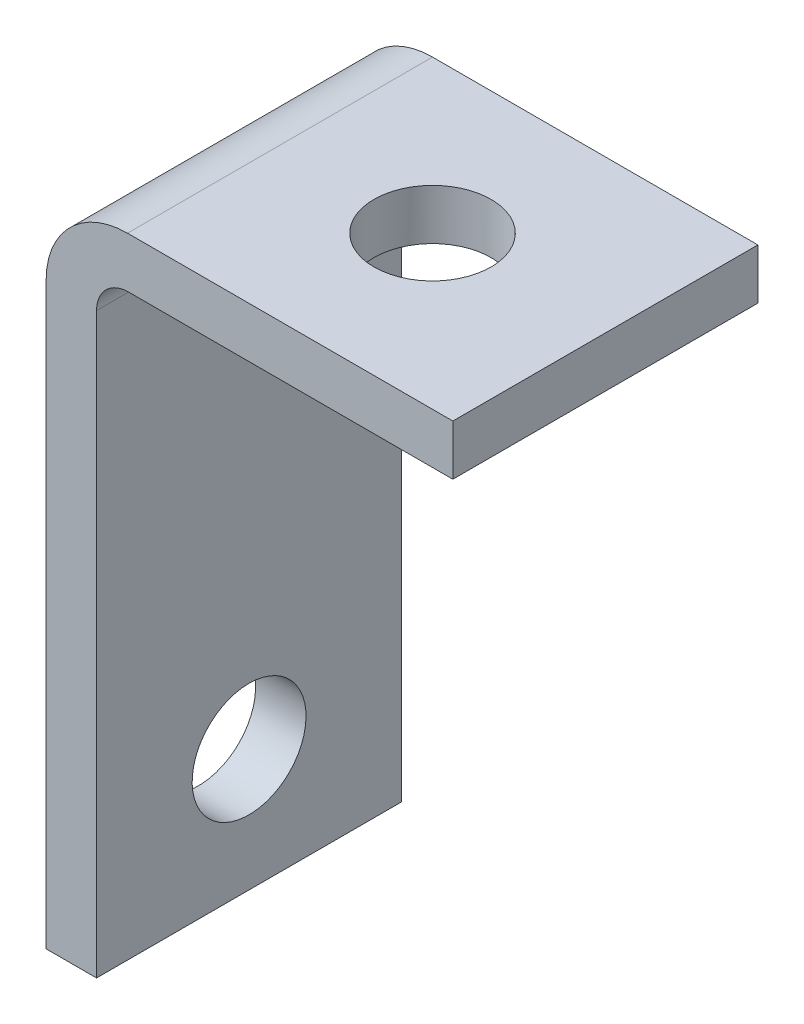
SolidWorks part; units mm, degrees
ref_plane "Front Plane" through (0, 0, 0) normal (0, 0, 1) x (1, 0, 0)
ref_plane "Top Plane" through (0, 0, 0) normal (0, 1, 0) x (1, 0, 0)
ref_plane "Right Plane" through (0, 0, 0) normal (1, 0, 0) x (0, 0, -1)
sketch "Sketch1" plane through (0, 0, 0) normal (0, 0, 1) x (1, 0, 0)
  line L0 (0, 0) -> (0, 20.6248)
  line L1 (0, 20.6248) -> (12.7, 20.6248)
  line L2 (12.7, 20.6248) -> (12.7, 19.05)
  line L3 (12.7, 19.05) -> (1.5748, 19.05)
  line L4 (1.5748, 19.05) -> (1.5748, 0)
  line L5 (1.5748, 0) -> (0, 0)
  dimension "D1" = 1.5748
  dimension "D2" = 19.05
  dimension "D3" = 12.7
extrude "Boss-Extrude1" add sketch "Sketch1" along normal blind 9.525
fillet "Fillet1" radius 1 1 edges at (1.5748, 19.05, 4.7625)
fillet "Fillet2" radius 2.54 1 edges at (0, 20.6248, 4.7625)
sketch "Sketch2" plane through (1.5748, 0, 0) normal (1, 0, 0) x (0, 0, -1)
  line L0 (-4.7625, 0) -> (-4.7625, 3.81) construction
  line L1 (-9.525, 0) -> (0, 0) construction
  circle A0 centre (-4.7625, 3.81) radius 1.778
  dimension "D1" = 3.556
  dimension "D2" = 3.81
extrude "Cut-Extrude1" cut sketch "Sketch2" against normal through all
sketch "Sketch3" plane through (0, 20.6248, 0) normal (0, 1, 0) x (1, 0, 0)
  line L0 (12.7, -4.7625) -> (7.3025, -4.7625) construction
  line L1 (12.7, -9.525) -> (12.7, 0) construction
  line L2 (0, -9.525) -> (0, 0) construction
  circle A0 centre (7.3025, -4.7625) radius 1.8288
  dimension "D1" = 3.6576
  dimension "D2" = 7.3025
extrude "Cut-Extrude2" cut sketch "Sketch3" against normal through all
